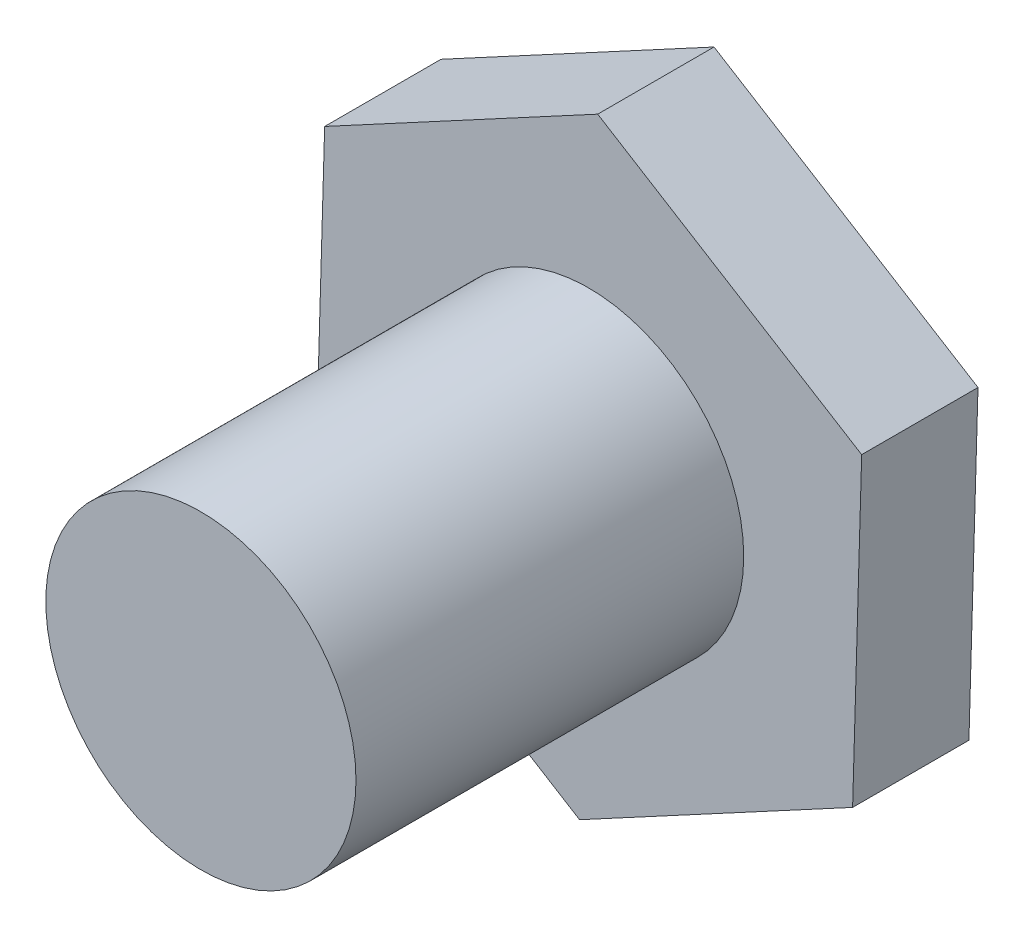
SolidWorks part; units mm, degrees
ref_plane "前视基准面" through (0, 0, 0) normal (0, 0, 1) x (1, 0, 0)
ref_plane "上视基准面" through (0, 0, 0) normal (0, 1, 0) x (1, 0, 0)
ref_plane "右视基准面" through (0, 0, 0) normal (1, 0, 0) x (0, 0, -1)
sketch "草图1" plane through (0, 0, 0) normal (0, 0, 1) x (1, 0, 0)
  line L1 (3.4041, -2.1004) -> (3.5211, 1.8979)
  line L2 (3.5211, 1.8979) -> (0.117, 3.9983)
  line L3 (0.117, 3.9983) -> (-3.4041, 2.1004)
  line L4 (-3.4041, 2.1004) -> (-3.5211, -1.8979)
  line L5 (-3.5211, -1.8979) -> (-0.117, -3.9983)
  line L6 (-0.117, -3.9983) -> (3.4041, -2.1004)
  circle A0 centre (0, 0) radius 3.4641 construction
  dimension "D1" = 4
extrude "凸台-拉伸1" add sketch "草图1" along normal blind 1.5
sketch "草图2" plane through (0, 0, 1.5) normal (0, 0, 1) x (1, 0, 0)
  circle A0 centre (0, 0) radius 2
  dimension "D1" = 4
extrude "凸台-拉伸2" add sketch "草图2" along normal blind 5
